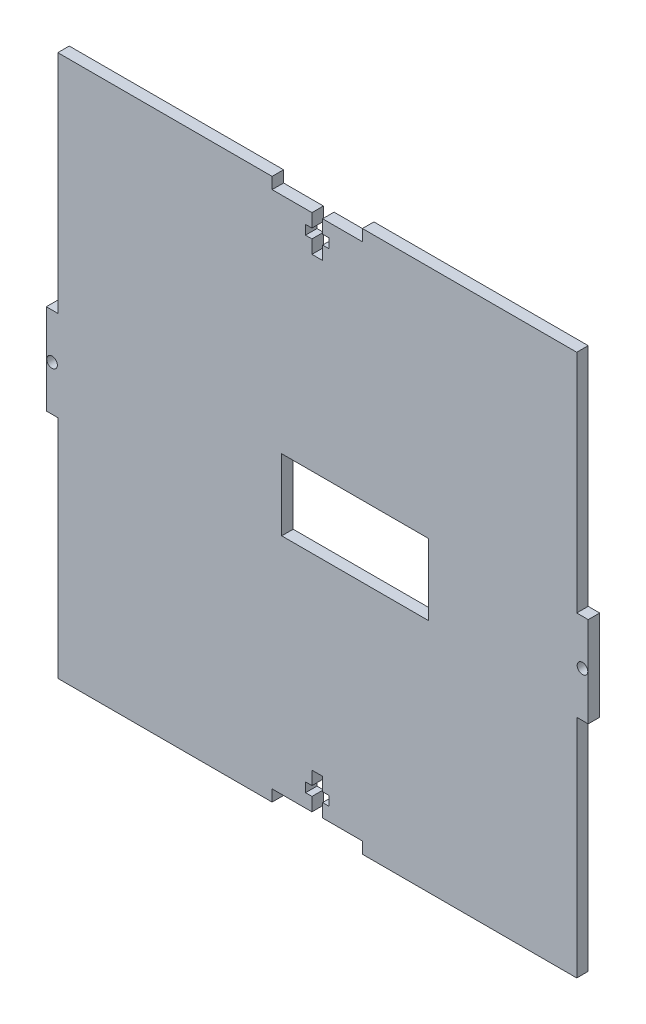
SolidWorks part; units mm, degrees
ref_plane "Front Plane" through (0, 0, 0) normal (0, 0, 1) x (1, 0, 0)
ref_plane "Top Plane" through (0, 0, 0) normal (0, 1, 0) x (1, 0, 0)
ref_plane "Right Plane" through (0, 0, 0) normal (1, 0, 0) x (0, 0, -1)
sketch "Sketch1" plane through (0, 0, 0) normal (0, 0, 1) x (1, 0, 0)
  line L0 (0, 75) -> (0, -75) construction
  line L1 (-71.825, 75) -> (71.825, 75)
  line L2 (-71.825, 75) -> (-71.825, -75)
  line L3 (-71.825, -75) -> (71.825, -75)
  line L4 (71.825, 75) -> (71.825, -75)
  line L5 (-71.825, 75) -> (71.825, -75) construction
  line L6 (-71.825, -75) -> (71.825, 75) construction
  line L7 (-71.825, 0) -> (71.825, 0) construction
  line L8 (-3.25, -65.525) -> (3.25, -65.525)
  line L9 (12.5, 75) -> (-12.5, 75)
  line L10 (12.5, 75) -> (12.5, 71.825)
  line L11 (12.5, 71.825) -> (-12.5, 71.825)
  line L12 (-12.5, 75) -> (-12.5, 71.825)
  line L13 (12.5, 75) -> (-12.5, 71.825) construction
  line L14 (12.5, 71.825) -> (-12.5, 75) construction
  line L15 (-1.47, 71.825) -> (1.47, 71.825)
  line L16 (-1.47, 71.825) -> (-1.47, 61.825)
  line L17 (-1.47, 61.825) -> (1.47, 61.825)
  line L18 (1.47, 71.825) -> (1.47, 61.825)
  line L19 (-1.47, 71.825) -> (1.47, 61.825) construction
  line L20 (-1.47, 61.825) -> (1.47, 71.825) construction
  line L21 (-3.25, 68.125) -> (3.25, 68.125)
  line L22 (-3.25, 68.125) -> (-3.25, 65.525)
  line L23 (-3.25, 65.525) -> (3.25, 65.525)
  line L24 (3.25, 68.125) -> (3.25, 65.525)
  line L25 (-3.25, 68.125) -> (3.25, 65.525) construction
  line L26 (-3.25, 65.525) -> (3.25, 68.125) construction
  line L27 (3.25, -68.125) -> (3.25, -65.525)
  line L28 (-3.25, -68.125) -> (3.25, -68.125)
  line L29 (-3.25, -68.125) -> (-3.25, -65.525)
  line L30 (-1.47, -61.825) -> (1.47, -61.825)
  line L31 (1.47, -71.825) -> (1.47, -61.825)
  line L32 (-1.47, -71.825) -> (1.47, -71.825)
  line L33 (-1.47, -71.825) -> (-1.47, -61.825)
  line L34 (12.5, -71.825) -> (-12.5, -71.825)
  line L35 (-12.5, -75) -> (-12.5, -71.825)
  line L36 (12.5, -75) -> (-12.5, -75)
  line L37 (12.5, -75) -> (12.5, -71.825)
  line L38 (75, -12.5) -> (71.825, -12.5)
  line L39 (-75, 12.5) -> (-71.825, 12.5)
  line L40 (-75, 12.5) -> (-75, -12.5)
  line L41 (-75, -12.5) -> (-71.825, -12.5)
  line L42 (-71.825, 12.5) -> (-71.825, -12.5)
  line L43 (-75, 12.5) -> (-71.825, -12.5) construction
  line L44 (-75, -12.5) -> (-71.825, 12.5) construction
  line L45 (71.825, 12.5) -> (71.825, -12.5)
  line L46 (75, 12.5) -> (71.825, 12.5)
  line L47 (75, 12.5) -> (75, -12.5)
  circle A0 centre (-73.4125, 0) radius 1.47
  circle A1 centre (73.4125, 0) radius 1.47
  point P0 (0, 0)
  point P10 (0, 73.4125)
  point P15 (0, 66.825)
  point P20 (0, 66.825)
  point P37 (-73.4125, 0)
  dimension "D11" = 2.94
  dimension "D1" = 150
  dimension "D2" = 150
  dimension "D3" = 3.175
  dimension "D4" = 10
  dimension "D5" = 2.94
  dimension "D6" = 25
  dimension "D7" = 6.5
  dimension "D8" = 2.6
  dimension "D9" = 6.3
  dimension "D10" = 3.175
extrude "Boss-Extrude1" add sketch "Sketch1" along normal mid plane 3.175 contours L21 L24 L23 L18 L17 L16 L22 L11 L12 L1 L2 L3 L4 L10 | L40 L39 L42 L41 | A0 | L38 L45 L46 L47 | A1
sketch "Sketch2" plane through (0, 0, 1.5875) normal (0, 0, 1) x (1, 0, 0)
  line L9 (-9.0805, -9.8425) -> (30.0955, -9.8425) construction
  line L10 (30.8575, 9.8425) -> (-9.8425, 9.8425)
  line L11 (30.8575, 9.8425) -> (30.8575, -9.8425)
  line L12 (30.8575, -9.8425) -> (-9.8425, -9.8425)
  line L13 (-9.8425, 9.8425) -> (-9.8425, -9.8425)
  line L14 (-9.8425, 9.0805) -> (-9.8425, -9.0805) construction
  line L15 (30.0955, 9.8425) -> (-9.0805, 9.8425) construction
  line L16 (30.8575, -9.0805) -> (30.8575, 9.0805) construction
extrude "Cut-Extrude1" cut sketch "Sketch2" against normal through all
